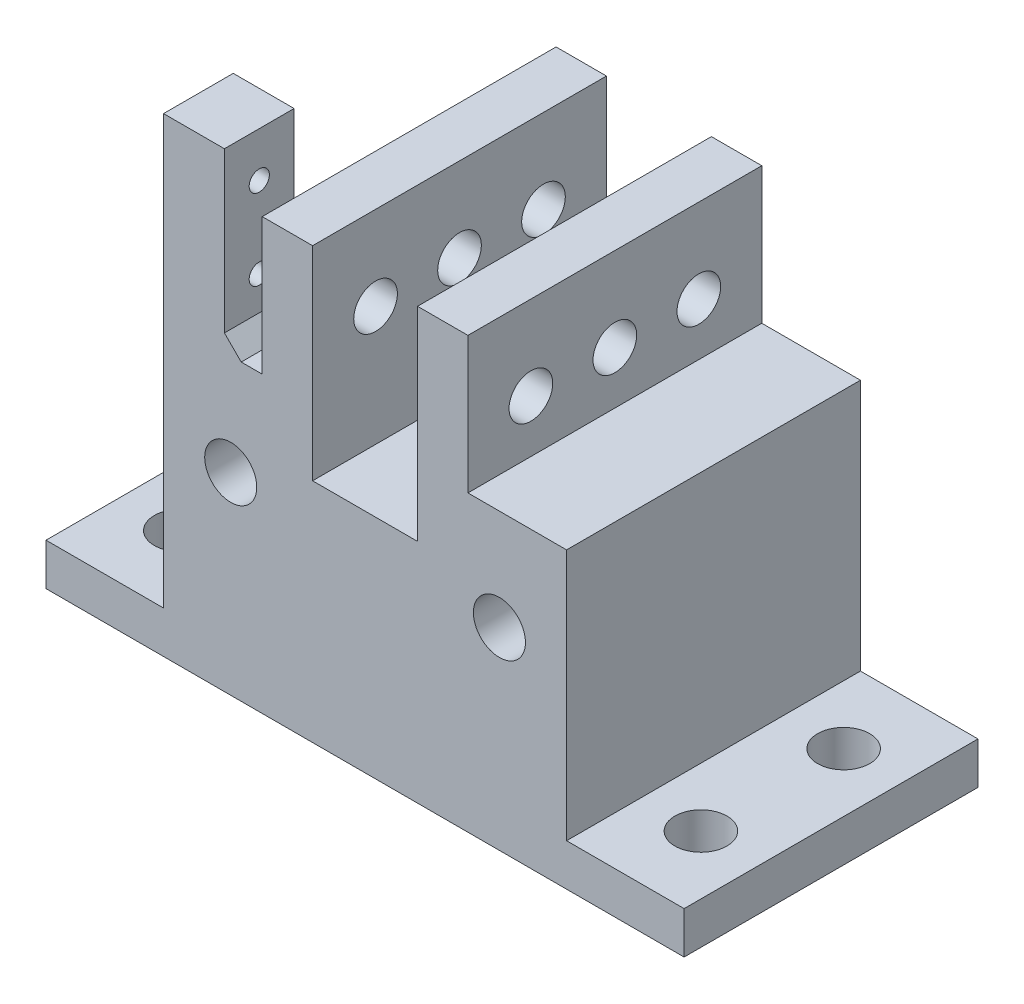
SolidWorks part; units mm, degrees
ref_plane "Front Plane" through (0, 0, 0) normal (0, 0, 1) x (1, 0, 0)
ref_plane "Top Plane" through (0, 0, 0) normal (0, 1, 0) x (1, 0, 0)
ref_plane "Right Plane" through (0, 0, 0) normal (1, 0, 0) x (0, 0, -1)
sketch "Sketch1" plane through (0, 0, 0) normal (0, 0, 1) x (1, 0, 0)
  line L1 (-5, -3.75) -> (-35, -3.75)
  line L2 (-35, -3.75) -> (-35, -28.75)
  line L3 (-35, -28.75) -> (13, -28.75)
  line L6 (-5, -3.75) -> (13, -3.75)
  line L7 (5, -15.75) -> (13, -15.75) construction
  line L8 (13, -28.75) -> (13, -3.75)
  circle A0 centre (5, -15.75) radius 3.1
  circle A1 centre (-27, -15.75) radius 3.1
  dimension "D5" = 6.2
  dimension "D6" = 6.2
  dimension "D1" = 8
  dimension "D2" = 8
  dimension "D3" = 32
  dimension "D4" = 12
extrude "Boss-Extrude1" add sketch "Sketch1" along normal blind 35
sketch "Sketch2" plane through (0, 0, 0) normal (0, 0, -1) x (-1, 0, 0)
  circle A0 centre (27, -15.75) radius 3.1 construction
  circle A1 centre (-5, -15.75) radius 3.1 construction
  circle A2 centre (27, -15.75) radius 3.1
  circle A3 centre (-5, -15.75) radius 3.1
extrude "Boss-Extrude2" add sketch "Sketch2" against normal blind 20
sketch "Sketch3" plane through (0, 0, 35) normal (0, 0, 1) x (1, 0, 0)
  line L0 (-11, -28.75) -> (-11, 2.5) construction
  line L1 (-35, -28.75) -> (13, -28.75) construction
  line L2 (-17.25, 2.5) -> (-4.75, 2.5) construction
  line L3 (-17.25, 2.5) -> (-17.25, -7.5)
  line L4 (-17.25, 2.5) -> (-17.25, 12.5)
  line L5 (-4.75, 2.5) -> (-4.75, -7.5)
  line L6 (-4.75, 2.5) -> (-4.75, 12.5)
  line L7 (-17.25, 12.5) -> (-23.25, 12.5)
  line L8 (-23.25, 12.5) -> (-23.25, -7.5)
  line L9 (-23.25, -7.5) -> (-17.25, -7.5)
  line L10 (1.25, -7.5) -> (-4.75, -7.5)
  line L11 (1.25, 12.5) -> (1.25, -7.5)
  line L12 (-4.75, 12.5) -> (1.25, 12.5)
  point P6 (-11, 2.5)
  dimension "D1" = 31.25
  dimension "D2" = 12.5
  dimension "D3" = 10
  dimension "D4" = 10
  dimension "D5" = 6
extrude "Boss-Extrude3" add sketch "Sketch3" against normal up to surface (35 mm away) up to face at (-11, -16.25, 0)
sketch "Sketch4" plane through (-23.25, 0, 0) normal (-1, 0, 0) x (0, 0, 1)
  line L0 (35, -7.5) -> (0, -7.5) construction
  line L1 (35, 12.5) -> (35, -7.5) construction
  line L2 (35, -28.75) -> (35, 2.5) construction
  line L3 (0, -3.75) -> (0, -28.75) construction
  line L4 (17.5, -7.5) -> (17.5, 2.5) construction
  circle A0 centre (17.5, 2.5) radius 2.6
  circle A1 centre (27.5, 2.5) radius 2.6
  circle A2 centre (7.5, 2.5) radius 2.6
  point P15 (0, 0)
  point P17 (12.4248, -1.4463)
  dimension "D2" = 5.2
  dimension "D3" = 5.2
  dimension "D4" = 5.2
  dimension "D6" = 10
  dimension "D1" = 10
  dimension "D5" = 10
extrude "Cut-Extrude1" cut sketch "Sketch4" against normal through all
sketch "Sketch6" plane through (0, 0, 35) normal (0, 0, 1) x (1, 0, 0)
  line L0 (-17.25, -3.75) -> (-17.25, -11.75)
  line L1 (-17.25, -11.75) -> (-4.75, -11.75)
  line L2 (-4.75, -11.75) -> (-4.75, -3.75)
  line L3 (-17.25, -3.75) -> (-4.75, -3.75)
extrude "Cut-Extrude2" cut sketch "Sketch6" against normal through all
sketch "Sketch7" plane through (0, -28.75, 0) normal (0, -1, 0) x (1, 0, 0)
  line L4 (-35, 0) -> (13, 0)
  line L5 (13, 0) -> (13, 35)
  line L6 (13, 35) -> (-35, 35)
  line L7 (-35, 35) -> (-35, 0)
  line L8 (-35, 0) -> (13, 0)
  line L9 (13, 0) -> (13, 35)
  line L10 (13, 35) -> (-35, 35)
  line L11 (-35, 35) -> (-35, 0)
  dimension "D1" = 0
extrude "Boss-Extrude4" add sketch "Sketch7" along normal blind 10
sketch "Sketch8" plane through (0, -38.75, 0) normal (0, -1, 0) x (1, 0, 0)
  line L0 (-35, 35) -> (-49, 35)
  line L1 (-49, 35) -> (-49, 0)
  line L2 (-49, 0) -> (-35, 0)
  line L3 (-11, 35) -> (-11, -5.7205) construction
  line L4 (13, 35) -> (-35, 35) construction
  line L5 (-35, 35) -> (-35, 0)
  line L7 (27, 0) -> (13, 0)
  line L8 (27, 35) -> (27, 0)
  line L9 (13, 35) -> (27, 35)
  line L10 (13, 35) -> (13, 0)
  circle A0 centre (-42, 9) radius 3.1
  circle A1 centre (20, 9) radius 3.1
  circle A2 centre (-42, 26) radius 3.1
  circle A3 centre (20, 26) radius 3.1
  dimension "D1" = 6.2
  dimension "6.2" = 6.2
  dimension "D3" = 6.2
  dimension "D4" = 9
  dimension "D6" = 9
  dimension "D7" = 9
  dimension "D5" = 9
extrude "Boss-Extrude5" add sketch "Sketch8" against normal blind 5
ref_plane "Plane1" through (-30.15, 41.3691, 256.7186) normal (1, 0, 0) x (0, 0, -1)
sketch "Sketch9" plane through (-30.15, 41.3691, 256.7186) normal (1, 0, 0) x (0, 0, -1)
  line L0 (225.8686, -29.4691) -> (225.8686, -39.0691) construction
  line L1 (230.0186, -24.1191) -> (230.0186, -45.1191)
  line L2 (221.7186, -45.1191) -> (256.7186, -45.1191) construction
  line L3 (230.0186, -45.1191) -> (230.0186, -49.1191)
  line L4 (230.0186, -49.1191) -> (221.7186, -49.1191)
  line L5 (221.7186, -49.1191) -> (221.7186, -24.1191)
  line L6 (221.7186, -24.1191) -> (230.0186, -24.1191)
  line L7 (230.0186, -45.1191) -> (221.7186, -45.1191)
  circle A0 centre (225.8686, -29.4691) radius 1.2
  circle A1 centre (225.8686, -39.0691) radius 1.2
  point P13 (221.7186, -36.6191)
  dimension "D1" = 4.15
  dimension "D2" = 4.15
  dimension "D3" = 21
  dimension "D4" = 4
extrude "Boss-Extrude6" add sketch "Sketch9" against normal up to surface (4.85 mm away) and the other way blind 2.4
chamfer "Chamfer1" distance 2 angle 45 2 edges at (-27.75, -3.75, 30.85) (-31.375, -3.75, 26.7)
